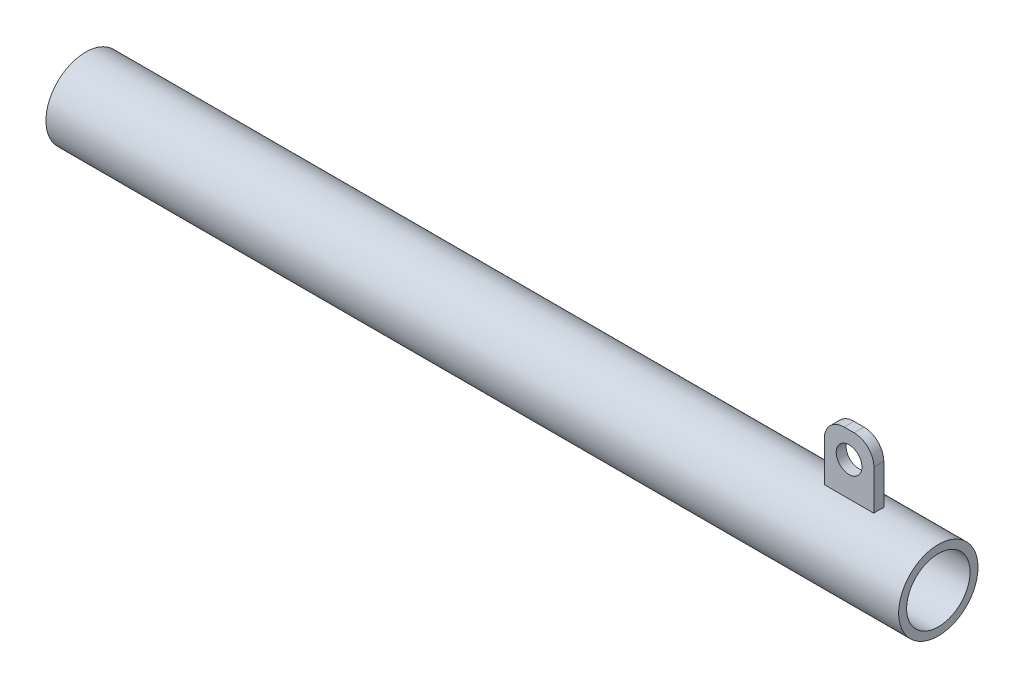
SolidWorks part; units mm, degrees
ref_plane "Front Plane" through (0, 0, 0) normal (0, 0, 1) x (1, 0, 0)
ref_plane "Top Plane" through (0, 0, 0) normal (0, 1, 0) x (1, 0, 0)
ref_plane "Right Plane" through (0, 0, 0) normal (1, 0, 0) x (0, 0, -1)
sketch "Sketch1" plane through (0, 0, 0) normal (1, 0, 0) x (0, 0, -1)
  circle A0 centre (0, 0) radius 20
  circle A1 centre (0, 0) radius 16
  dimension "D1" = 40
  dimension "D2" = 32
extrude "Boss-Extrude1" add sketch "Sketch1" against normal blind 430
ref_plane "Plane1" through (0, 50, 0) normal (0, 1, 0) x (1, 0, 0)
sketch "Sketch2" plane through (0, 50, 0) normal (0, 1, 0) x (1, 0, 0)
  line L0 (0, 0) -> (-473.2116, 0) construction
  line L1 (0, -20) -> (0, 20) construction
  line L2 (-55, 2.5) -> (-30, 2.5)
  line L3 (-55, 2.5) -> (-55, -2.5)
  line L4 (-55, -2.5) -> (-30, -2.5)
  line L5 (-30, 2.5) -> (-30, -2.5)
  line L6 (-55, 2.5) -> (-30, -2.5) construction
  line L7 (-55, -2.5) -> (-30, 2.5) construction
  point P3 (-42.5, 0)
  point P8 (-46.7571, 0)
  dimension "D1" = 25
  dimension "D2" = 5
  dimension "D3" = 30
extrude "Boss-Extrude2" add sketch "Sketch2" against normal up to surface (30.1569 mm away)
fillet "Fillet1" radius 10 2 edges at (-30, 50, 0) (-55, 50, 0)
sketch "Sketch3" plane through (0, 0, 2.5) normal (0, 0, 1) x (1, 0, 0)
  line L0 (-42.5, 50) -> (-42.5, 19.8431) construction
  line L1 (-45, 50) -> (-40, 50) construction
  line L2 (-30, 19.8431) -> (-55, 19.8431) construction
  circle A0 centre (-42.5, 37) radius 6.5
  point P8 (0, 0)
  dimension "D1" = 13
  dimension "D2" = 13
extrude "Cut-Extrude1" cut sketch "Sketch3" against normal blind 10
